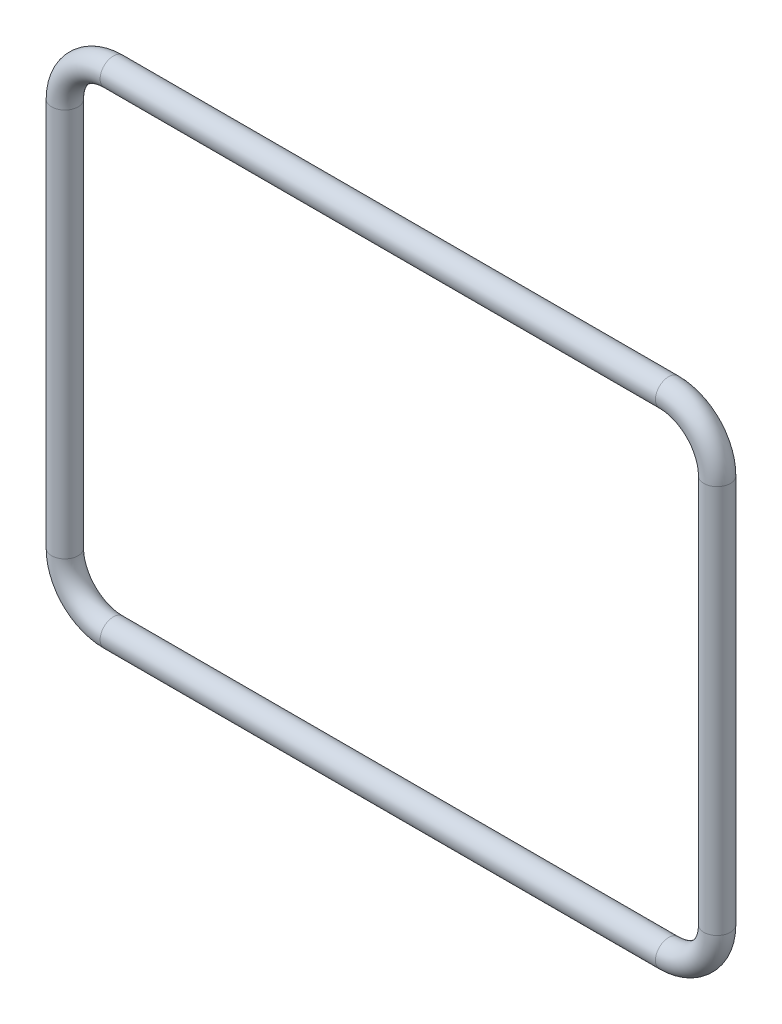
SolidWorks part; units mm, degrees
material "AISI 4130 Aço, normalizado a 870C"
ref_plane "Plano frontal" through (0, 0, 0) normal (0, 0, 1) x (1, 0, 0)
ref_plane "Plano superior" through (0, 0, 0) normal (0, 1, 0) x (1, 0, 0)
ref_plane "Plano direito" through (0, 0, 0) normal (1, 0, 0) x (0, 0, -1)
sketch "Esboço1" plane through (0, 0, 0) normal (0, 0, 1) x (1, 0, 0)
  line L0 (-100, 140) -> (-100, 0) construction
  line L1 (0, 0) -> (-200, 0) construction
  line L2 (0, 0) -> (0, 140) construction
  line L3 (0, 140) -> (-200, 140) construction
  line L4 (-200, 0) -> (-200, 140) construction
  line L5 (-200, 157.4625) -> (0, 157.4625)
  line L6 (-217.4625, 140) -> (-217.4625, 0)
  line L7 (-200, -17.4625) -> (0, -17.4625)
  line L8 (17.4625, 0) -> (17.4625, 140)
  line L9 (-200, 157.4625) -> (-200, 152.7) construction
  circle A0 centre (0, 0) radius 12.7 construction
  circle A1 centre (-200, 0) radius 12.7 construction
  circle A2 centre (-200, 140) radius 12.7 construction
  circle A3 centre (0, 140) radius 12.7 construction
  circle A4 centre (-200, 140) radius 17.4625 construction
  circle A5 centre (0, 140) radius 17.4625 construction
  circle A6 centre (-200, 0) radius 17.4625 construction
  circle A7 centre (0, 0) radius 17.4625 construction
  arc A8 (-200, 157.4625) -> (-217.4625, 140) centre (-200, 140) ccw
  arc A9 (-200, -17.4625) -> (-217.4625, 0) centre (-200, 0) cw
  arc A10 (17.4625, 0) -> (0, -17.4625) centre (0, 0) cw
  arc A11 (17.4625, 140) -> (0, 157.4625) centre (0, 140) ccw
  dimension "D1" = 25.4
  dimension "D2" = 140
  dimension "D3" = 200
  dimension "D4" = 4.7625
ref_plane "Plano1" through (-200, 0, 0) normal (1, 0, 0) x (0, 0, -1)
sketch "Esboço4" plane through (-200, 0, 0) normal (1, 0, 0) x (0, 0, -1)
  circle A0 centre (0, 157.4625) radius 4.7625
sweep "Varredura1" add profiles "Esboço4" path "Esboço1"
ref_plane "Plano2" through (0, 0, 10) normal (0, 0, 1) x (1, 0, 0)
ref_plane "Plano3" through (-100, 0, 0) normal (1, 0, 0) x (0, 0, -1)
